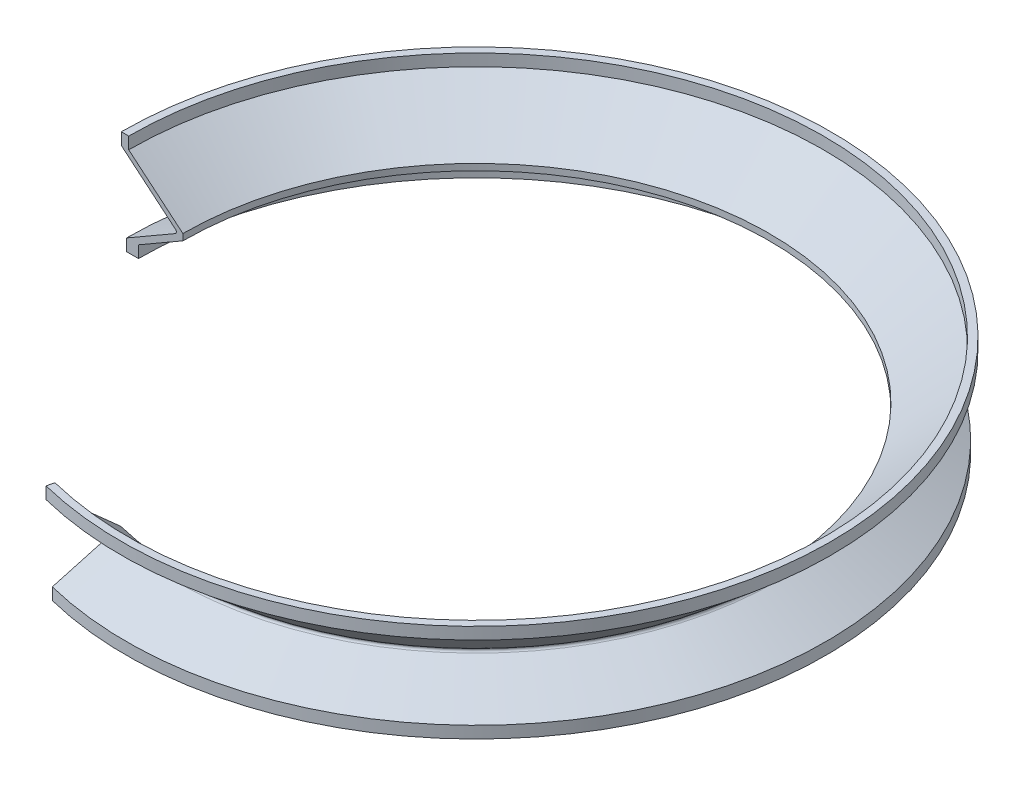
SolidWorks part; units mm, degrees
ref_plane "Front Plane" through (0, 0, 0) normal (0, 0, 1) x (1, 0, 0)
ref_plane "Top Plane" through (0, 0, 0) normal (0, 1, 0) x (1, 0, 0)
ref_plane "Right Plane" through (0, 0, 0) normal (1, 0, 0) x (0, 0, -1)
sketch "Sketch1" plane through (0, 0, 0) normal (0, 0, 1) x (1, 0, 0)
  line L0 (-42.6436, 0) -> (43.9692, 0) construction
  line L1 (0.6628, 0) -> (-8.8712, 8)
  line L2 (0.6628, 0) -> (-7.9975, -5)
  line L3 (1.4628, -0.6928) -> (-5.9975, -5)
  line L5 (-8.8712, 8) -> (-7.6267, 8)
  line L6 (-7.9975, -5) -> (-5.9975, -5)
  line L7 (50.6988, 7.609) -> (50.6988, -7.609) construction
  line L8 (2.3996, -0.152) -> (-16.3835, 15.6089) construction
  line L9 (0.6628, 0) -> (-17.0263, 14.8429) construction
  line L10 (0.6628, 0) -> (-17.9865, -10.7671) construction
  line L11 (2.3996, -0.152) -> (-17.4865, -11.6332) construction
  line L12 (0.6628, 0) -> (2.2628, 0) construction
  line L13 (1.4628, -0.6928) -> (1.4628, 0.373)
  line L14 (1.4628, 0.373) -> (-7.6267, 8)
  point P11 (1.4628, 0)
  dimension "D1" = 40
  dimension "D2" = 30
  dimension "D4" = 8
  dimension "D5" = 5
  dimension "D6" = 59.57
  dimension "D7" = 1.6
  dimension "D8" = 0.8
  dimension "D3" = 1
revolve "Revolve1" add sketch "Sketch1" angle 284 about L7
scale "Scale1" [suppressed]
fillet "Fillet2" radius 0.4 1 edges at (90.1276, 0, -30.8052)
sketch "Sketch2" plane through (0, 8, 0) normal (0, 1, 0) x (1, 0, 0)
  line L0 (36.5886, -56.5929) -> (36.2875, -57.8005) construction
  line L1 (-7.6267, 0) -> (-8.8712, 0) construction
  line L2 (36.5886, -56.5929) -> (36.2875, -57.8005)
  line L3 (-7.6267, 0) -> (-8.8712, 0)
  circle A0 centre (50.6988, 0) radius 59.57 construction
  circle A1 centre (50.6988, 0) radius 58.3254 construction
  arc A2 (36.2875, -57.8005) -> (-8.8712, 0) centre (50.6988, 0) ccw
  arc A3 (36.5886, -56.5929) -> (-7.6267, 0) centre (50.6988, 0) ccw
extrude "Boss-Extrude1" add sketch "Sketch2" along normal blind 2
sketch "Sketch3" plane through (0, -5, 0) normal (0, -1, 0) x (1, 0, 0)
  line L0 (36.4989, 56.9527) -> (36.9827, 55.0121) construction
  line L1 (-7.9975, 0) -> (-5.9975, 0) construction
  line L2 (36.4989, 56.9527) -> (36.9827, 55.0121)
  line L3 (-7.9975, 0) -> (-5.9975, 0)
  circle A0 centre (50.6988, 0) radius 56.6962 construction
  circle A1 centre (50.6988, 0) radius 58.6962 construction
  arc A2 (-5.9975, 0) -> (36.9827, 55.0121) centre (50.6988, 0) ccw
  arc A3 (-7.9975, 0) -> (36.4989, 56.9527) centre (50.6988, 0) ccw
extrude "Boss-Extrude2" add sketch "Sketch3" along normal blind 2
